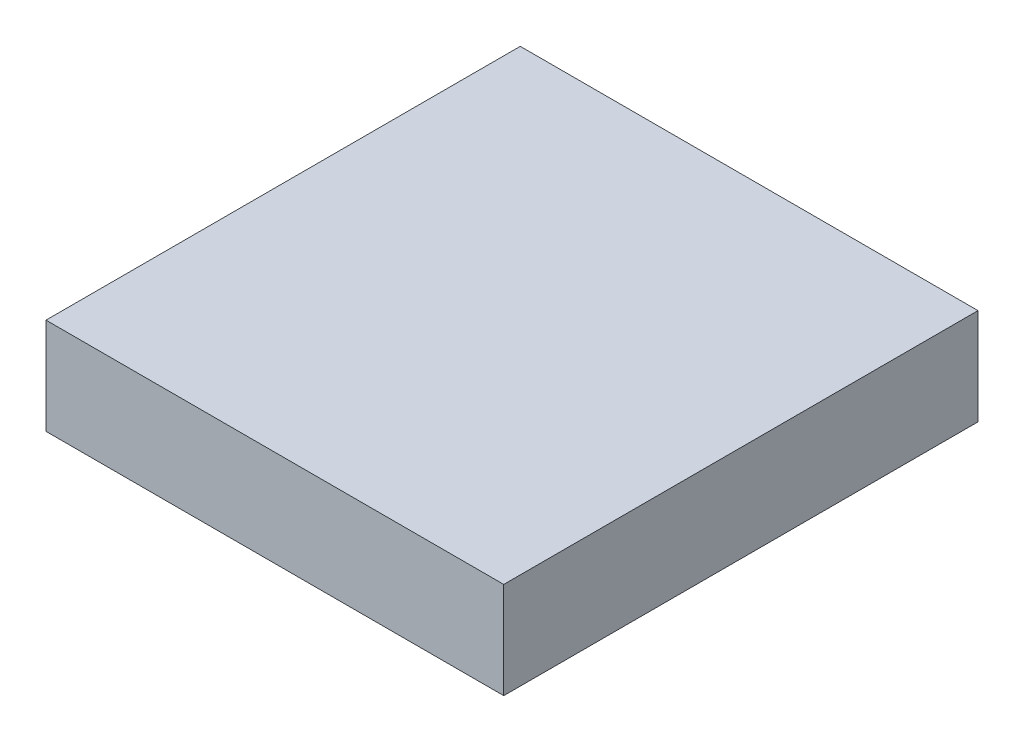
SolidWorks part; units mm, degrees
ref_plane "Front Plane" through (0, 0, 0) normal (0, 0, 1) x (1, 0, 0)
ref_plane "Top Plane" through (0, 0, 0) normal (0, 1, 0) x (1, 0, 0)
ref_plane "Right Plane" through (0, 0, 0) normal (1, 0, 0) x (0, 0, -1)
sketch "Sketch1" plane through (0, 0, 0) normal (0, 0, 1) x (1, 0, 0)
  line L0 (-0.4826, 0.1016) -> (0.4826, 0.1016)
  line L1 (0.4826, 0.1016) -> (0.4826, -0.1016)
  line L2 (0.4826, -0.1016) -> (-0.4826, -0.1016)
  line L3 (-0.4826, -0.1016) -> (-0.4826, 0.1016)
extrude "Component_Outline" add sketch "Sketch1" along normal blind 1 separate body
sketch3d "3DSketch1"
  line L0 (0, 0, 0) -> (1, 0, 0)
  line L1 (0, 0, 0) -> (0, 1, 0)
  line L2 (0, 0, 0) -> (0, 0, 1)
  point P0 (0, 0, 0)
